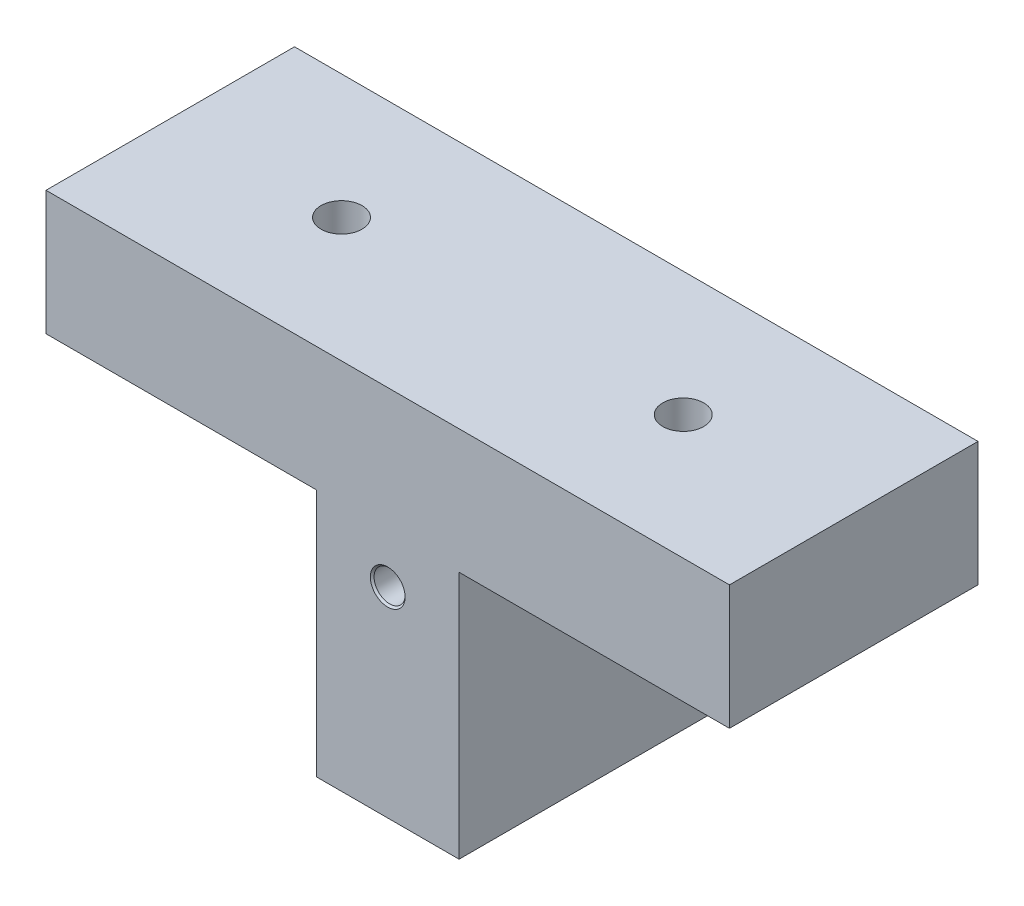
SolidWorks part; units mm, degrees
ref_plane "Front Plane" through (0, 0, 0) normal (0, 0, 1) x (1, 0, 0)
ref_plane "Top Plane" through (0, 0, 0) normal (0, 1, 0) x (1, 0, 0)
ref_plane "Right Plane" through (0, 0, 0) normal (1, 0, 0) x (0, 0, -1)
sketch "Sketch1" plane through (0, 0, 0) normal (0, 0, 1) x (1, 0, 0)
  line L0 (5.7407, -5) -> (27.5, -5)
  line L1 (-27.5, 5) -> (27.5, 5)
  line L2 (-27.5, 5) -> (-27.5, -5)
  line L3 (-27.5, -5) -> (-5.7407, -5)
  line L4 (27.5, 5) -> (27.5, -5)
  line L9 (-5.7407, -25) -> (5.7407, -25)
  line L10 (5.7407, -5) -> (5.7407, -25)
  line L13 (-5.7407, -5) -> (-5.7407, -25)
  point P0 (0, 0)
  point P6 (0, 0)
  dimension "D1" = 55
  dimension "D2" = 10
  dimension "D3" = 20
extrude "Boss-Extrude1" add sketch "Sketch1" along normal blind 20
sketch "Sketch2" plane through (0, 0, 20) normal (0, 0, 1) x (1, 0, 0)
  line L0 (27.5, 5) -> (-27.5, 5) construction
  point P0 (0, 0)
  point P1 (0, -8.9)
  dimension "D1" = 13.9
sketch "Sketch4" plane through (0, -5, 0) normal (0, -1, 0) x (1, 0, 0)
  point P0 (0, 0)
  point P1 (0, 0)
  point P3 (13.78, 0)
  point P4 (0, 0)
  point P5 (-13.72, 0)
  point P6 (13.78, 10)
  point P7 (0, 10)
  point P8 (-13.72, 10)
  dimension "D1" = 13.78
  dimension "D2" = 13.72
  dimension "D3" = 10
  dimension "D4" = 10
  dimension "D5" = 10
sketch "Sketch7" plane through (0, 5, 0) normal (0, 1, 0) x (1, 0, 0)
  line L0 (27.5, 0) -> (-27.5, 0) construction
  point P0 (0, 0)
  point P1 (-12.7327, 0)
  point P3 (0, 0)
  point P6 (14.295, 0)
sketch "Sketch8" plane through (0, 5, 0) normal (0, 1, 0) x (1, 0, 0)
  line L0 (27.5, -20) -> (-27.5, -20) construction
  line L1 (-27.5, -20) -> (-27.5, 0) construction
  line L3 (27.5, -20) -> (27.5, 0) construction
  point P0 (0, -20)
  point P1 (0, -10)
  point P4 (-13.72, -20)
  point P5 (0, -20)
  point P6 (13.72, -20)
  point P7 (13.72, -10)
  point P8 (-13.72, -10)
  dimension "D1" = 10
  dimension "D2" = 13.72
  dimension "D3" = 13.72
  dimension "D4" = 27.5
  dimension "D5" = 10
  dimension "D6" = 27.5
hole_wizard "Tap Drill for M3 Tap1" positions "3DSketch2" profile "Sketch10" hole size "M3" standard "ISO" end condition through all
sketch3d "3DSketch2"
  point P0 (0, -8.9, 20)
sketch "Sketch10" plane through (0, -8.9, 20) normal (1, 0, 0) x (0, -1, 0)
  line L0 (0, 0) -> (0, 20)
  line L1 (0, 20) -> (1.25, 20)
  line L2 (1.25, 20) -> (1.25, 0.15)
  line L3 (1.25, 0.15) -> (1.4, 0)
  line L5 (1.4, 0) -> (0, 0)
  line L6 (-1.25, 0.15) -> (-1.4, 0) construction
  line L11 (0, -6.35) -> (0, 107.95) construction
  dimension "Thru Hole Dia." = 2.5
  dimension "Thru Hole Depth" = 20
  dimension "Near C'Sink Dia." = 2.8
  dimension "Near C'Sink Angle" = 90
hole_wizard "Tap Drill for M4 Tap1" positions "3DSketch3" profile "Sketch11" hole size "M4" standard "ISO" end condition through all
sketch3d "3DSketch3"
  point P0 (13.78, -5, 10)
  point P3 (-13.72, -5, 10)
sketch "Sketch11" plane through (13.78, -5, 10) normal (1, 0, 0) x (0, 0, -1)
  line L0 (0, 0) -> (0, 10)
  line L1 (0, 10) -> (1.65, 10)
  line L2 (1.65, 10) -> (1.65, 0.025)
  line L3 (1.65, 0.025) -> (1.675, 0)
  line L5 (1.675, 0) -> (0, 0)
  line L6 (-1.65, 0.025) -> (-1.675, 0) construction
  line L11 (0, -6.35) -> (0, 107.95) construction
  dimension "Thru Hole Dia." = 3.3
  dimension "Thru Hole Depth" = 10
  dimension "Near C'Sink Dia." = 3.35
  dimension "Near C'Sink Angle" = 90
